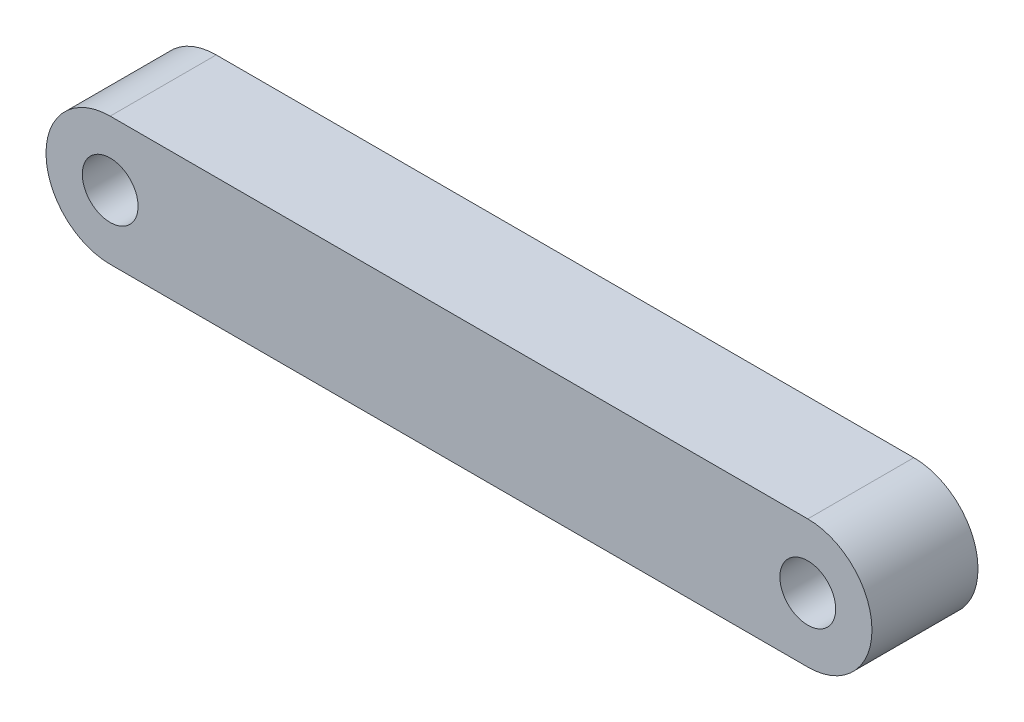
SolidWorks part; units mm, degrees
ref_plane "Спереди" through (0, 0, 0) normal (0, 0, 1) x (1, 0, 0)
ref_plane "Сверху" through (0, 0, 0) normal (0, 1, 0) x (1, 0, 0)
ref_plane "Справа" through (0, 0, 0) normal (1, 0, 0) x (0, 0, -1)
sketch "Sketch1" plane through (0, 0, 0) normal (0, 0, 1) x (1, 0, 0)
  line L0 (0, 0) -> (25, 0) construction
  line L1 (0, 0) -> (25, 0) construction
  line L2 (0, 2.3) -> (25, 2.3)
  line L3 (0, -2.3) -> (25, -2.3)
  arc A0 (0, 2.3) -> (0, -2.3) centre (0, 0) ccw
  arc A1 (25, -2.3) -> (25, 2.3) centre (25, 0) ccw
  circle A2 centre (0, 0) radius 1
  circle A3 centre (25, 0) radius 1
  point P3 (12.5, 0)
  point P8 (12.5, -2.3)
  dimension "D3" = 2
  dimension "D1" = 25
  dimension "D2" = 4.6
extrude "Boss-Extrude1" add sketch "Sketch1" along normal blind 3.8
